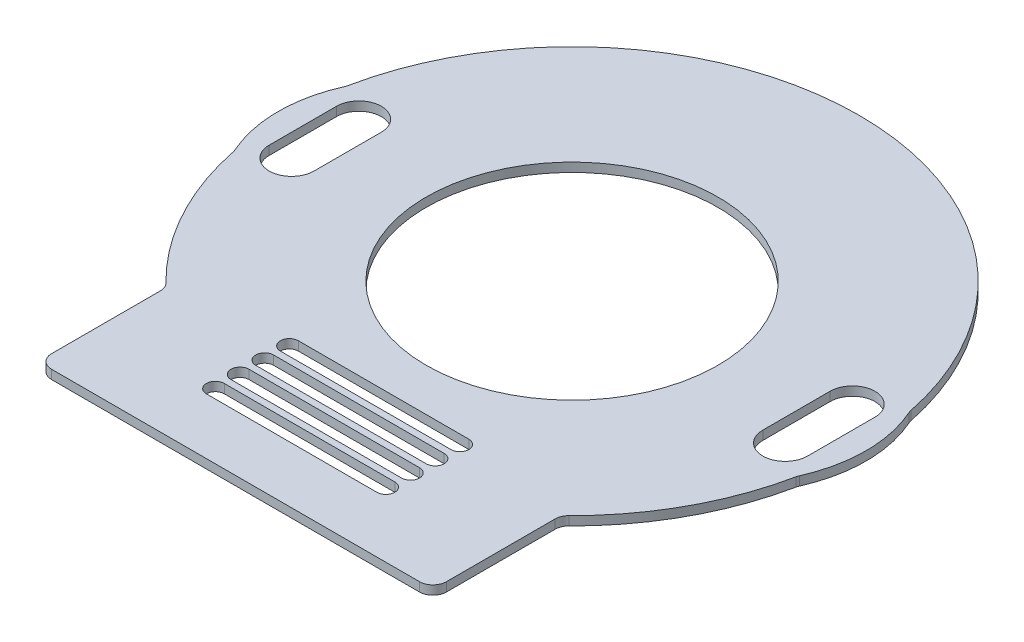
SolidWorks part; units mm, degrees
ref_plane "Front Plane" through (0, 0, 0) normal (0, 0, 1) x (1, 0, 0)
ref_plane "Top Plane" through (0, 0, 0) normal (0, 1, 0) x (1, 0, 0)
ref_plane "Right Plane" through (0, 0, 0) normal (1, 0, 0) x (0, 0, -1)
sketch "Sketch1" plane through (0, 0, 0) normal (0, 1, 0) x (1, 0, 0)
  line L0 (0, 0) -> (0, 17.7897) construction
  line L1 (-55, 7.5) -> (-55, -7.5) construction
  line L2 (-50, 7.5) -> (-50, -7.5)
  line L3 (-60, 7.5) -> (-60, -7.5)
  line L4 (55, 7.5) -> (55, -7.5) construction
  line L5 (50, 7.5) -> (50, -7.5)
  line L6 (60, 7.5) -> (60, -7.5)
  line L7 (-41, -75) -> (41, -75)
  line L8 (-44, -72) -> (-44, -47.7493)
  line L9 (44, -72) -> (44, -47.7493)
  line L10 (-19, -44) -> (19, -44) construction
  line L11 (-19, -42) -> (19, -42)
  line L12 (-19, -46) -> (19, -46)
  line L13 (-19, -49.5) -> (19, -49.5) construction
  line L14 (-19, -47.5) -> (19, -47.5)
  line L15 (-19, -51.5) -> (19, -51.5)
  line L16 (-19, -55) -> (19, -55) construction
  line L17 (-19, -53) -> (19, -53)
  line L18 (-19, -57) -> (19, -57)
  line L19 (-19, -60.5) -> (19, -60.5) construction
  line L20 (-19, -58.5) -> (19, -58.5)
  line L21 (-19, -62.5) -> (19, -62.5)
  arc A0 (-62.7019, -12.8248) -> (-44.8955, -45.6113) centre (0, 0) ccw
  circle A1 centre (0, 0) radius 32.5
  arc A2 (-62.9005, 12.2054) -> (-62.9005, -12.2054) centre (-35.4956, 0) ccw
  arc A3 (-50, 7.5) -> (-60, 7.5) centre (-55, 7.5) ccw
  arc A4 (-60, -7.5) -> (-50, -7.5) centre (-55, -7.5) ccw
  arc A5 (50, 7.5) -> (60, 7.5) centre (55, 7.5) cw
  arc A6 (60, -7.5) -> (50, -7.5) centre (55, -7.5) cw
  arc A7 (62.9005, 12.2054) -> (62.9005, -12.2054) centre (35.4956, 0) cw
  arc A8 (62.7019, 12.8248) -> (-62.7019, 12.8248) centre (0, 0) ccw
  arc A9 (44.8955, -45.6113) -> (62.7019, -12.8248) centre (0, 0) ccw
  arc A10 (-62.7019, 12.8248) -> (-62.9005, 12.2054) centre (-65.641, 13.426) cw
  arc A11 (-62.9005, -12.2054) -> (-62.7019, -12.8248) centre (-65.641, -13.426) cw
  arc A12 (62.7019, -12.8248) -> (62.9005, -12.2054) centre (65.641, -13.426) cw
  arc A13 (62.7019, 12.8248) -> (62.9005, 12.2054) centre (65.641, 13.426) ccw
  arc A14 (44, -47.7493) -> (44.8955, -45.6113) centre (47, -47.7493) cw
  arc A15 (-44, -47.7493) -> (-44.8955, -45.6113) centre (-47, -47.7493) ccw
  arc A16 (41, -75) -> (44, -72) centre (41, -72) ccw
  arc A17 (-41, -75) -> (-44, -72) centre (-41, -72) cw
  arc A18 (-19, -42) -> (-19, -46) centre (-19, -44) ccw
  arc A19 (19, -46) -> (19, -42) centre (19, -44) ccw
  arc A20 (-19, -47.5) -> (-19, -51.5) centre (-19, -49.5) ccw
  arc A21 (19, -51.5) -> (19, -47.5) centre (19, -49.5) ccw
  arc A22 (-19, -53) -> (-19, -57) centre (-19, -55) ccw
  arc A23 (19, -57) -> (19, -53) centre (19, -55) ccw
  arc A24 (-19, -58.5) -> (-19, -62.5) centre (-19, -60.5) ccw
  arc A25 (19, -62.5) -> (19, -58.5) centre (19, -60.5) ccw
  point P8 (-55, 0)
  point P16 (-55, 12.5)
  point P19 (55, 0)
  point P30 (0, -75)
  point P32 (-62.7674, 12.5)
  point P35 (-62.7674, -12.5)
  point P38 (62.7674, -12.5)
  point P41 (62.7674, 12.5)
  point P44 (44, -46.4758)
  point P49 (44, -75)
  point P52 (-44, -75)
  point P55 (0, -44)
  point P64 (0, -49.5)
  point P71 (0, -55)
  point P78 (0, -60.5)
  dimension "D1" = 128
  dimension "D2" = 65
  dimension "D8" = 3
  dimension "D12" = 30
  dimension "D3" = 55
  dimension "D4" = 10
  dimension "D5" = 15
  dimension "D6" = 88
  dimension "D7" = 75
  dimension "D9" = 38
  dimension "D10" = 4
  dimension "D11" = 31
  dimension "D13" = 4
extrude "Boss-Extrude1" add sketch "Sketch1" along normal blind 2
